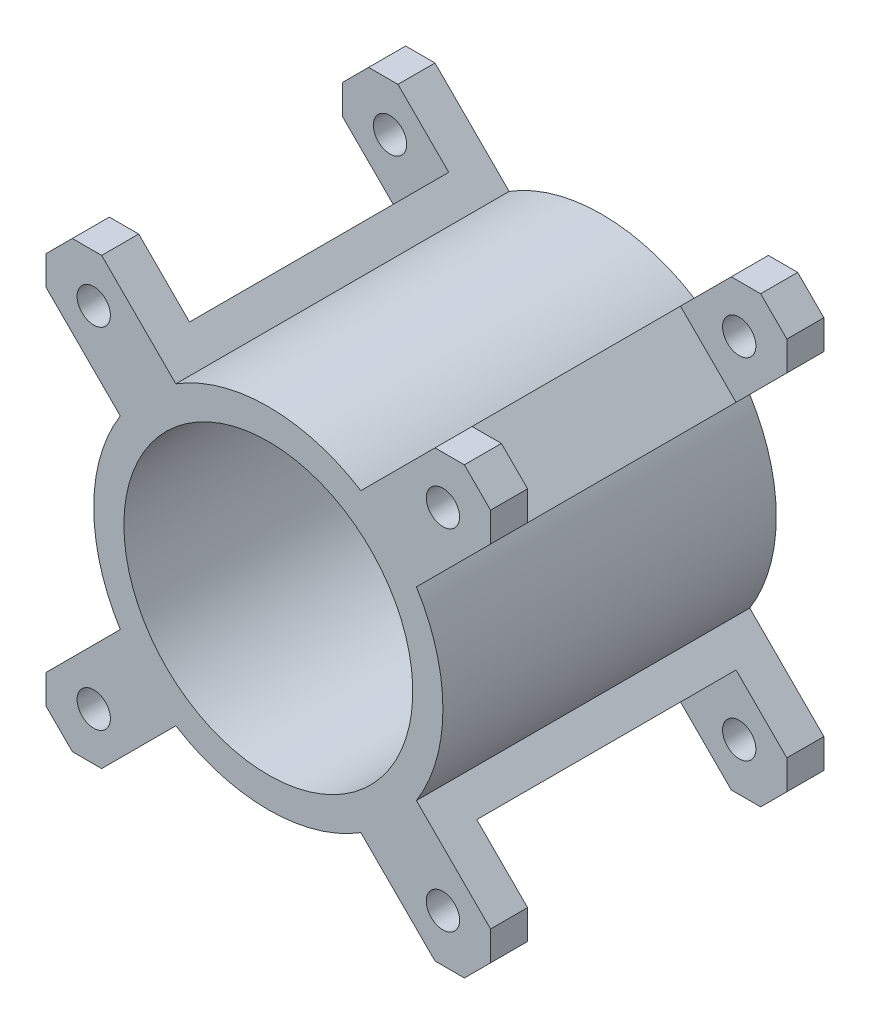
SolidWorks part; units mm, degrees
ref_plane "Front Plane" through (0, 0, 0) normal (0, 0, 1) x (1, 0, 0)
ref_plane "Top Plane" through (0, 0, 0) normal (0, 1, 0) x (1, 0, 0)
ref_plane "Right Plane" through (0, 0, 0) normal (1, 0, 0) x (0, 0, -1)
sketch "Sketch1" plane through (0, 0, 0) normal (0, 0, 1) x (1, 0, 0)
  line L0 (30, 60) -> (30, 0) construction
  line L1 (0, 0) -> (60, 0)
  line L2 (0, 0) -> (0, 60)
  line L3 (0, 60) -> (60, 60)
  line L4 (60, 0) -> (60, 60)
  line L5 (0, 30) -> (60, 30) construction
  line L6 (7.5, 60) -> (20.4811, 47.0189)
  line L7 (6.43, 53.57) -> (53.57, 53.57) construction
  line L8 (6.43, 53.57) -> (6.43, 6.43) construction
  line L9 (6.43, 6.43) -> (53.57, 6.43) construction
  line L10 (53.57, 53.57) -> (53.57, 6.43) construction
  line L11 (0, 60) -> (60, 0) construction
  line L12 (0, 52.5) -> (12.9811, 39.5189)
  line L13 (60, 52.5) -> (47.0189, 39.5189)
  line L14 (52.5, 60) -> (39.5189, 47.0189)
  line L15 (60, 7.5) -> (47.0189, 20.4811)
  line L16 (52.5, 0) -> (39.5189, 12.9811)
  line L17 (7.5, 0) -> (20.4811, 12.9811)
  line L18 (0, 7.5) -> (12.9811, 20.4811)
  circle A0 centre (6.43, 53.57) radius 2.25
  circle A1 centre (53.57, 53.57) radius 2.25
  circle A2 centre (6.43, 6.43) radius 2.25
  circle A3 centre (53.57, 6.43) radius 2.25
  circle A4 centre (30, 30) radius 19.5
  circle A5 centre (30, 30) radius 23.57
  dimension "D5" = 4.5
  dimension "D6" = 39
  dimension "D1" = 60
  dimension "D2" = 60
  dimension "D3" = 47.14
  dimension "D4" = 47.14
  dimension "D7" = 7.5
extrude "Boss-Extrude1" add sketch "Sketch1" along normal blind 45 contours A5 L6 L3 L2 L12 A0 | L6 A5 L12 A4 | L14 A5 L6 A4 | L13 A5 L14 A4 | A5 L13 L4 L3 L14 A1 | L15 A5 L13 A4 | A5 L16 L1 L4 L15 A3 | L17 A5 L16 A4 | L18 A5 L17 A4 | A5 L18 L2 L1 L17 A2 | L16 A5 L15 A4 | L12 A5 L18 A4
chamfer "Chamfer1" distance 3.5355 angle 45 4 edges at (60, 60, 22.5) (0, 60, 22.5) (0, 0, 22.5) (60, 0, 22.5)
sketch "Sketch2" plane through (58.2322, 58.2322, 0) normal (0.7071, 0.7071, 0) x (0, 0, -1)
  line L1 (-5, 5.3033) -> (-40, 5.3033)
  line L2 (-5, 5.3033) -> (-5, -5.3033)
  line L3 (-5, -5.3033) -> (-40, -5.3033)
  line L4 (-40, 5.3033) -> (-40, -5.3033)
  line L6 (-45, 5.3033) -> (0, 5.3033) construction
  line L7 (-45, -5.3033) -> (0, -5.3033) construction
  line L8 (-45, 5.3033) -> (-45, 2.5) construction
  dimension "D1" = 5
  dimension "D2" = 5
extrude "Cut-Extrude1" cut sketch "Sketch2" against normal blind 12.5
pattern_circular "CirPattern1" count 4 over 360 about axis through (30, 30, 0) along (0, 0, 1) of "Cut-Extrude1"
